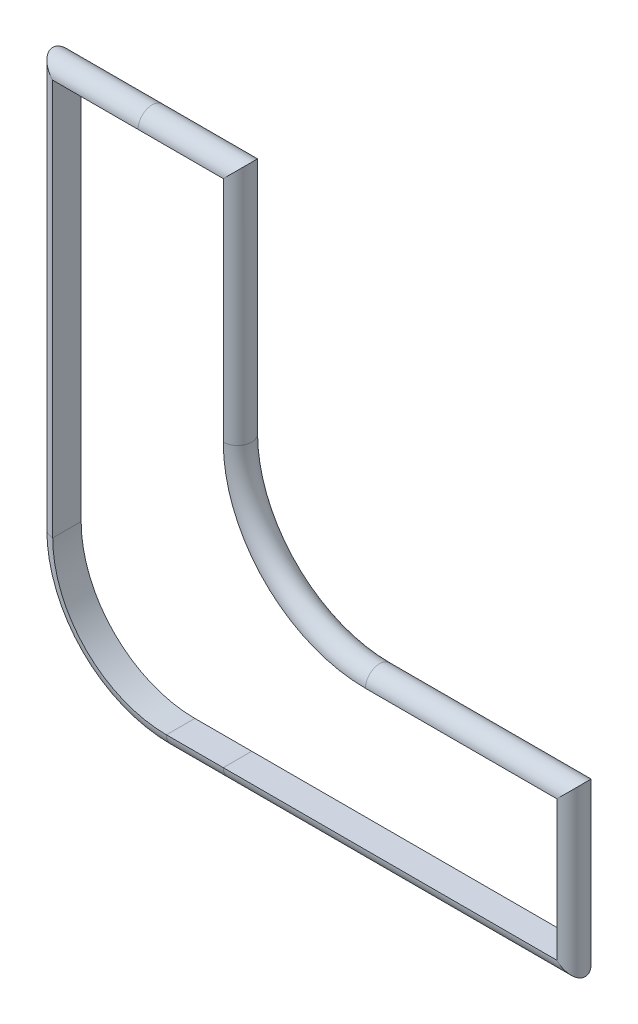
SolidWorks part; units mm, degrees
ref_plane "Front Plane" through (0, 0, 0) normal (0, 0, 1) x (1, 0, 0)
ref_plane "Top Plane" through (0, 0, 0) normal (0, 1, 0) x (1, 0, 0)
ref_plane "Right Plane" through (0, 0, 0) normal (1, 0, 0) x (0, 0, -1)
sketch "Sketch2" plane through (0, 0, 0) normal (0, 0, 1) x (1, 0, 0)
  line L0 (-0.15, 0.35) -> (0.15, 0.35)
  line L1 (0.7368, -0.3014) -> (0.7368, -0.5473)
  line L2 (0.15, -0.5473) -> (0.7368, -0.5473)
  line L3 (-0.15, 0.35) -> (-0.15, -0.3473)
  line L4 (0.05, -0.5473) -> (0.15, -0.5473)
  line L6 (0.15, 0.35) -> (0.15, -0.0514)
  line L7 (0.4, -0.3014) -> (0.7368, -0.3014)
  arc A0 (0.4, -0.3014) -> (0.15, -0.0514) centre (0.4, -0.0514) cw
  arc A1 (0.05, -0.5473) -> (-0.15, -0.3473) centre (0.05, -0.3473) cw
  dimension "D1" = 0.25
  dimension "D2" = 0.2
sketch "Sketch1" plane through (0, 0, 0) normal (1, 0, 0) x (0, 0, -1)
  line L0 (-0.025, 0.35) -> (0.025, 0.35)
  arc A0 (0.025, 0.35) -> (-0.025, 0.35) centre (0, 0.35) ccw
  dimension "D1" = 0.05
  dimension "D2" = 0.05
sweep "Sweep1" add profiles "Sketch1" path "Sketch2"
